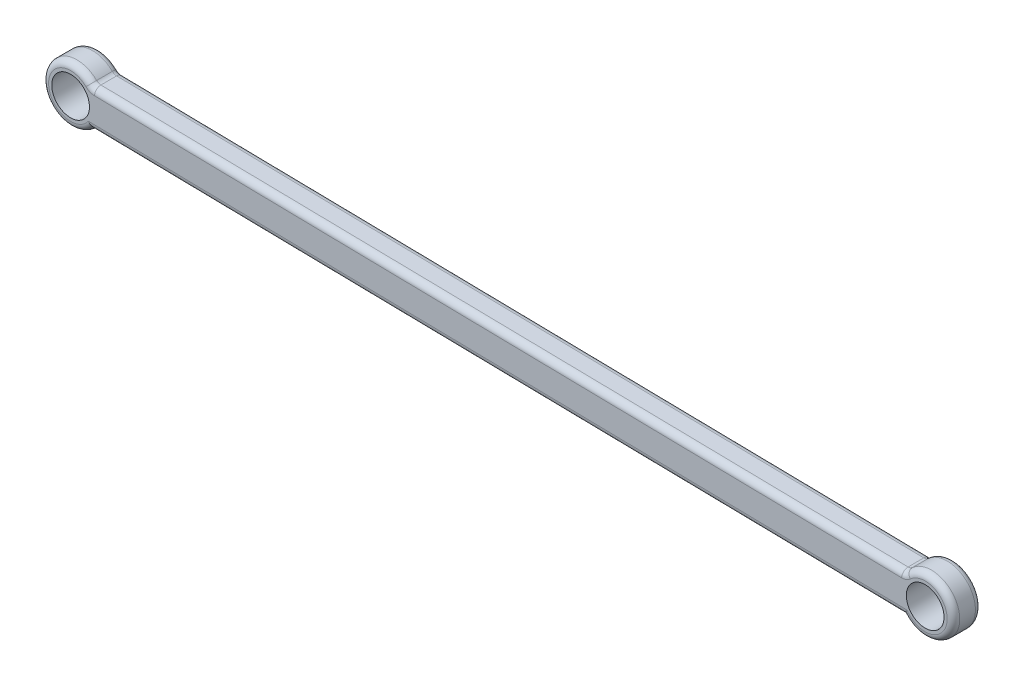
SolidWorks part; units mm, degrees
ref_plane "Front Plane" through (0, 0, 0) normal (0, 0, 1) x (1, 0, 0)
ref_plane "Top Plane" through (0, 0, 0) normal (0, 1, 0) x (1, 0, 0)
ref_plane "Right Plane" through (0, 0, 0) normal (1, 0, 0) x (0, 0, -1)
sketch "Sketch1" plane through (0, 0, 0) normal (0, 0, 1) x (1, 0, 0)
  line L0 (0, 0) -> (135.98, -2.3339) construction
  line L1 (3.4051, 2.942) -> (132.6778, 0.7232)
  line L2 (3.3021, -3.0571) -> (132.5749, -5.2759)
  arc A0 (0.0515, 2.9996) -> (-0.0515, -2.9996) centre (0, 0) ccw
  arc A1 (135.9285, -5.3335) -> (136.0315, 0.6657) centre (135.98, -2.3339) ccw
  arc A2 (3.4051, 2.942) -> (3.3021, -3.0571) centre (0, 0) ccw
  arc A3 (132.5749, -5.2759) -> (132.6778, 0.7232) centre (135.98, -2.3339) ccw
  circle A4 centre (0, 0) radius 3
  circle A5 centre (135.98, -2.3339) radius 3
  point P3 (67.99, -1.1669)
  dimension "D1" = 3
  dimension "D3" = 9
  dimension "D2" = 136
extrude "Boss-Extrude1" add sketch "Sketch1" along normal blind 4.5
fillet "Fillet3" radius 1 10 edges at (140.4793, -2.4111, 4.5) (140.4793, -2.4111, 0) (-4.4993, 0.0772, 4.5) (-4.4993, 0.0772, 0) (132.6778, 0.7232, 2.25) (68.0415, 1.8326, 4.5) (3.4051, 2.942, 2.25) (68.0415, 1.8326, 0) (67.9385, -4.1665, 0) (67.9385, -4.1665, 4.5)
